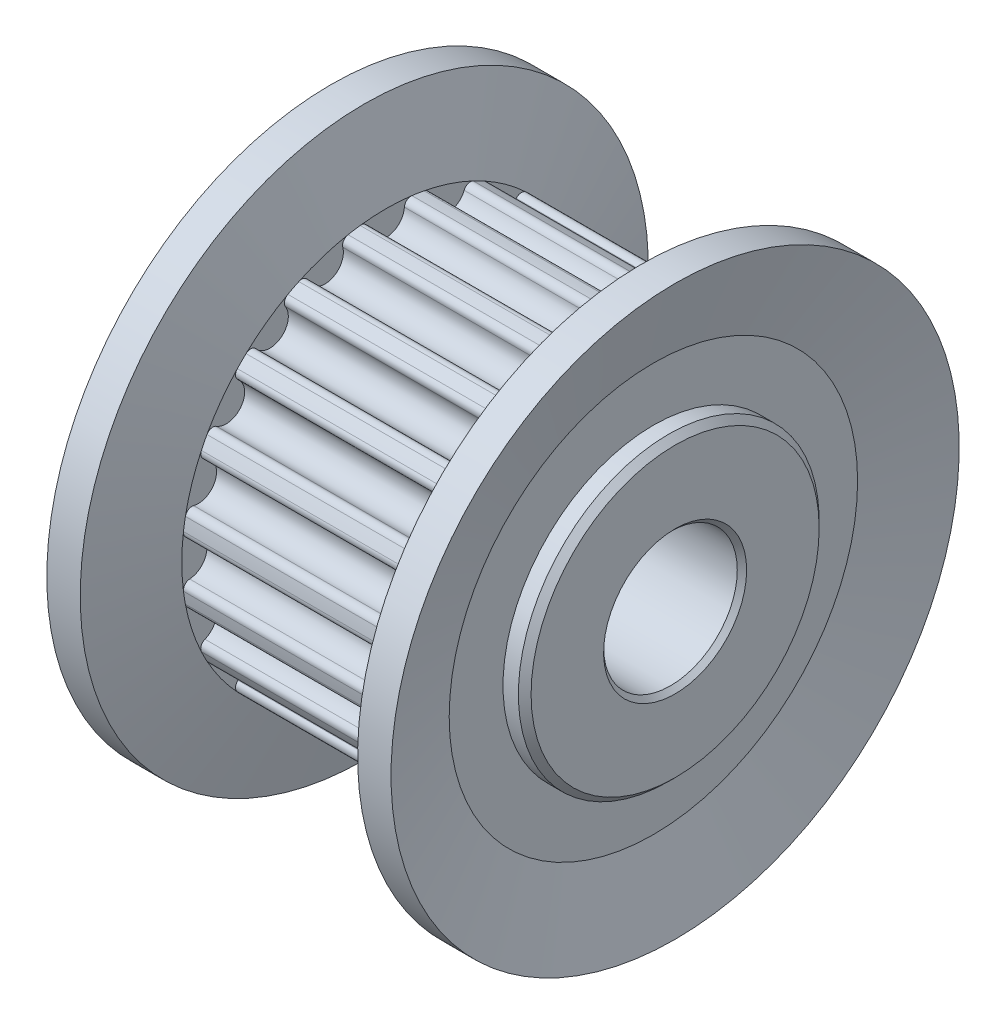
SolidWorks part; units mm, degrees
ref_plane "前视基准面" through (0, 0, 0) normal (0, 0, 1) x (1, 0, 0)
ref_plane "上视基准面" through (0, 0, 0) normal (0, 1, 0) x (1, 0, 0)
ref_plane "右视基准面" through (0, 0, 0) normal (1, 0, 0) x (0, 0, -1)
sketch "草图1" plane through (0, 0, 0) normal (1, 0, 0) x (0, 0, -1)
  line L0 (0, 0) -> (20, 0)
  line L1 (0, 0) -> (0, 6.365) construction
  line L6 (-1.5, 1.3229) -> (1.5, 1.3229)
  line L7 (-1.5, 1.3229) -> (-1.5, 3.4)
  line L8 (-1.5, 3.4) -> (1.5, 3.4)
  line L9 (1.5, 1.3229) -> (1.5, 3.4)
  circle A0 centre (0, 0) radius 6.365
  arc A1 (-0.7738, 6.0608) -> (6.11, 0) centre (0, 0) ccw
  circle A6 centre (0, 0) radius 2
  arc A18 (-0.5489, 5.8751) -> (0.5489, 5.8751) centre (0, 5.91) ccw
  arc A19 (-0.7738, 6.0608) -> (-0.5489, 5.8751) centre (-0.7485, 5.8624) cw
  arc A20 (0.7738, 6.0608) -> (0.5489, 5.8751) centre (0.7485, 5.8624) ccw
  point P8 (0, 5.36)
  point P20 (0, 6.11)
  point P26 (0, 2)
  dimension "D1" = 0.2
  dimension "PD" = 12.73
  dimension "OD" = 12.22
  dimension "H" = 4
  dimension "D2" = 0.75
  dimension "D3" = 0.2
  dimension "齿数" = 20
  dimension "t" = 1.4
  dimension "b" = 3
sketch "草图2" plane through (0, 0, 0) normal (0, 0, 1) x (1, 0, 0)
  line L0 (0, 0) -> (10.3, 0) construction
  line L1 (0, 0) -> (0, 4.5)
  line L2 (0, 4.5) -> (1.65, 4.5)
  line L3 (1.65, 4.5) -> (1.65, 6.11)
  line L4 (1.65, 6.11) -> (8.65, 6.11)
  line L5 (8.65, 6.11) -> (8.65, 4.5)
  line L6 (8.65, 4.5) -> (10.3, 4.5)
  line L7 (10.3, 4.5) -> (10.3, 0)
  line L8 (0, 0) -> (0, 6.365) construction
  line L9 (0.65, 4.5) -> (0.65, 6.11)
  line L10 (0.65, 6.11) -> (0, 8.5)
  line L11 (0, 8.5) -> (1, 8.5)
  line L12 (1, 8.5) -> (1.65, 6.11)
  line L13 (1.65, 6.11) -> (1.65, 4.5)
  line L14 (5.15, 6.11) -> (5.15, 0) construction
  line L15 (7.15, 6.11) -> (7.15, 0)
  line L17 (10.3, 0.5) -> (7.3, 0.5)
  line L18 (0, 0.5) -> (3, 0.5)
  point P27 (3, 0.5)
  dimension "A" = 7
  dimension "W" = 10.3
  dimension "E" = 9
  dimension "D2" = 1.65
  dimension "D3" = 1
  dimension "F" = 17
  dimension "M" = 4
  dimension "S" = 3
  dimension "R" = 1
  dimension "T" = 3
  dimension "Q" = 1
  dimension "J" = 3
  dimension "Z" = 1
sketch "草图3" plane through (0, 0, 0) normal (0, 0, 1) x (1, 0, 0)
  line L0 (0, 0) -> (0, 4.31)
  line L1 (0.19, 4.5) -> (1.65, 4.5)
  line L2 (1.65, 4.5) -> (1.65, 6.11)
  line L3 (1.65, 6.11) -> (8.65, 6.11)
  line L4 (8.65, 6.11) -> (8.65, 4.5)
  line L5 (8.65, 4.5) -> (10.11, 4.5)
  line L6 (10.3, 4.31) -> (10.3, 0)
  line L7 (10.3, 0) -> (0, 0)
  line L8 (0, 4.31) -> (0.19, 4.5)
  line L9 (10.11, 4.5) -> (10.3, 4.31)
  point P1 (0, 4.5)
  point P13 (10.3, 4.5)
  dimension "D1" = 0.19
  dimension "D2" = 45
  dimension "D4" = 45
revolve "旋转1" add sketch "草图3" angle 360 about L7
sketch "草图4" plane through (0, 0, 0) normal (1, 0, 0) x (0, 0, -1)
  arc A0 (0.7738, 6.0608) -> (-0.7738, 6.0608) centre (0, 0) ccw
  arc A1 (-0.7738, 6.0608) -> (6.11, 0) centre (0, 0) ccw construction
  arc A2 (-0.5489, 5.8751) -> (-0.7738, 6.0608) centre (-0.7485, 5.8624) ccw construction
  arc A3 (-0.5489, 5.8751) -> (0.5489, 5.8751) centre (0, 5.91) ccw construction
  arc A4 (0.7738, 6.0608) -> (0.5489, 5.8751) centre (0.7485, 5.8624) ccw construction
  arc A5 (-0.5489, 5.8751) -> (-0.7738, 6.0608) centre (-0.7485, 5.8624) ccw
  arc A8 (-0.5489, 5.8751) -> (0.5489, 5.8751) centre (0, 5.91) ccw
  arc A12 (0.7738, 6.0608) -> (0.5489, 5.8751) centre (0.7485, 5.8624) ccw
extrude "切除-拉伸1" cut sketch "草图4" along normal up to vertex (8.65 mm away) from vertex at 1.65 starting at point (1.65, 6.11, 0)
pattern_circular "阵列(圆周)1" count 20 over 360 about axis through (0, 0, 0) along (1, 0, 0) of "切除-拉伸1"
sketch "草图5" plane through (0, 0, 0) normal (0, 0, 1) x (1, 0, 0)
  line L0 (1, 8.5) -> (1.65, 6.11) construction
  line L1 (0, 8.5) -> (1, 8.5) construction
  line L2 (0.65, 6.11) -> (0, 8.5) construction
  line L3 (0.65, 4.5) -> (0.65, 6.11) construction
  line L4 (1.65, 4.5) -> (1.65, 6.11) construction
  line L5 (1, 8.5) -> (1.65, 6.11)
  line L6 (0, 8.5) -> (1, 8.5)
  line L7 (0.65, 6.11) -> (0, 8.5)
  line L8 (0.65, 4.5) -> (0.65, 6.11)
  line L9 (1.65, 4.5) -> (1.65, 6.11)
  line L10 (0.65, 4.5) -> (1.65, 4.5)
  line L11 (0, 0) -> (10.3, 0) construction
  line L12 (5.15, 6.11) -> (5.15, 0) construction
  line L13 (9.65, 4.5) -> (8.65, 4.5)
  line L14 (9.65, 4.5) -> (9.65, 6.11)
  line L15 (9.65, 6.11) -> (10.3, 8.5)
  line L16 (10.3, 8.5) -> (9.3, 8.5)
  line L17 (9.3, 8.5) -> (8.65, 6.11)
  line L18 (8.65, 4.5) -> (8.65, 6.11)
revolve "旋转2" add sketch "草图5" angle 360 about L11
sketch "草图6" plane through (0, 0, 0) normal (1, 0, 0) x (0, 0, -1)
  circle A0 centre (0, 0) radius 2 construction
  circle A1 centre (0, 0) radius 2
extrude "切除-拉伸2" cut sketch "草图6" along normal through all
chamfer "倒角1" distance 0.14 angle 45 2 edges at (0, 0, -2) (10.3, 0, -2)
